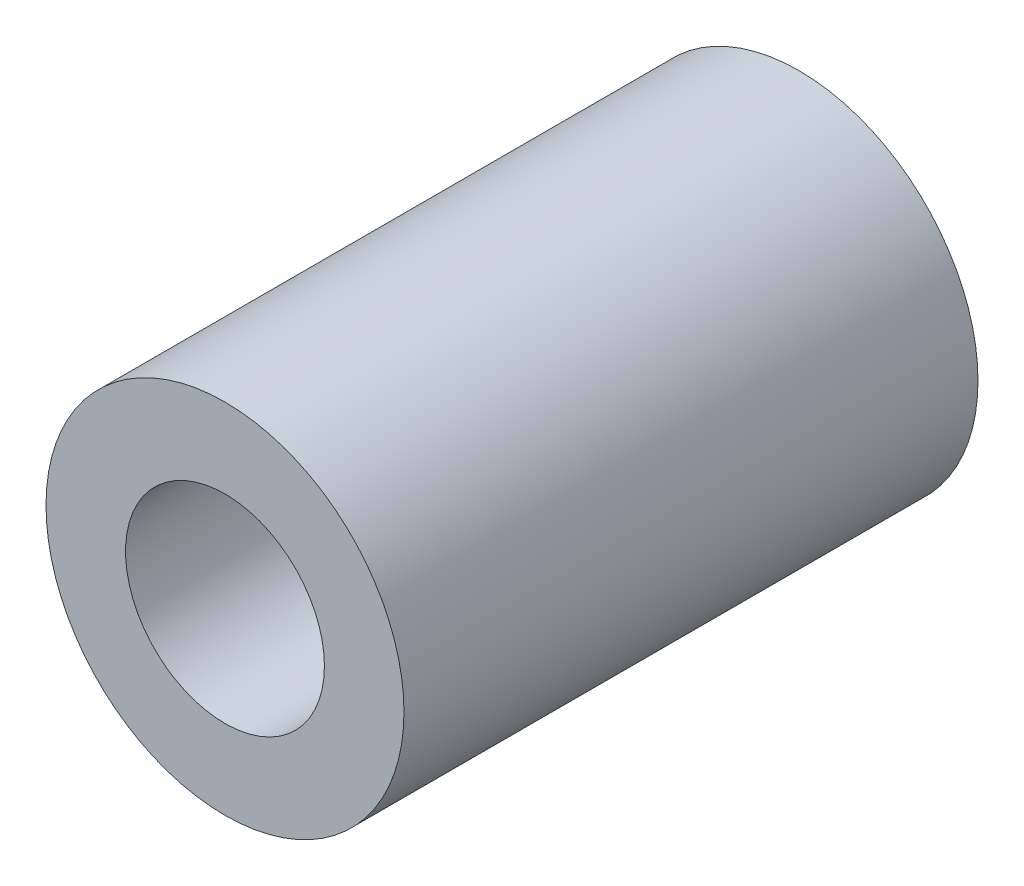
SolidWorks part; units mm, degrees
material "AISI 4340 Steel, annealed"
ref_plane "Front Plane" through (0, 0, 0) normal (0, 0, 1) x (1, 0, 0)
ref_plane "Top Plane" through (0, 0, 0) normal (0, 1, 0) x (1, 0, 0)
ref_plane "Right Plane" through (0, 0, 0) normal (1, 0, 0) x (0, 0, -1)
sketch "Sketch1" plane through (0, 0, 0) normal (0, 0, 1) x (1, 0, 0)
  circle A0 centre (0, 0) radius 7.1438
  circle A1 centre (0, 0) radius 3.9688
  dimension "D1" = 14.2875
  dimension "D2" = 7.9375
extrude "Boss-Extrude1" add sketch "Sketch1" against normal blind 22.9108
